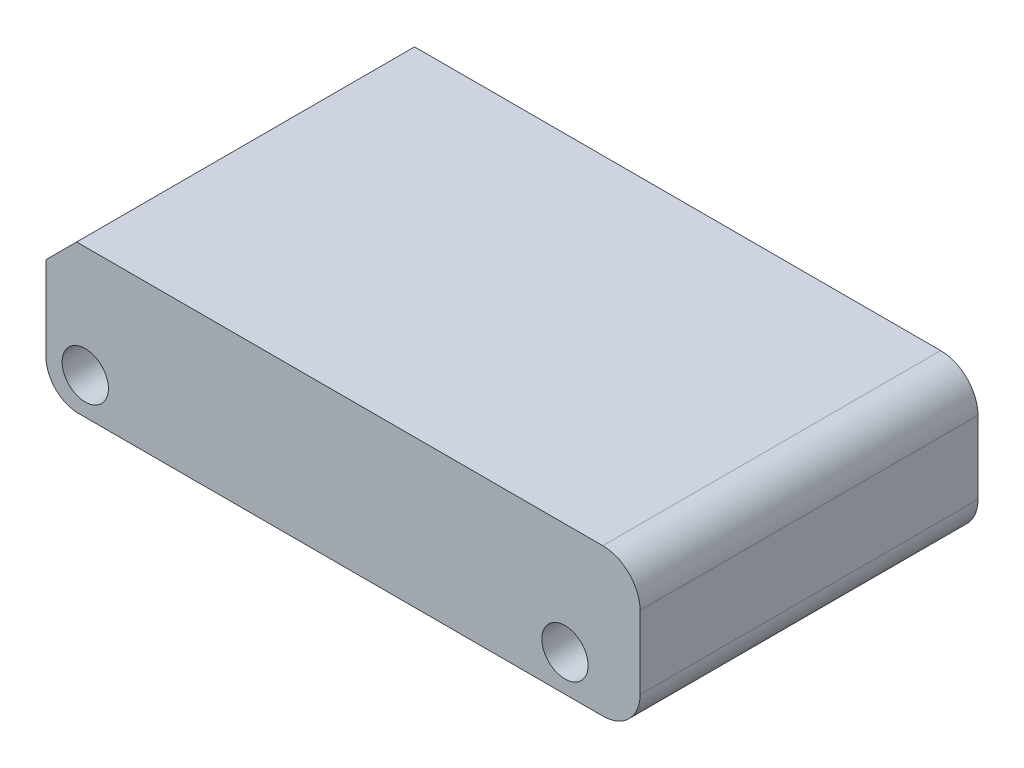
SolidWorks part; units mm, degrees
ref_plane "Front Plane" through (0, 0, 0) normal (0, 0, 1) x (1, 0, 0)
ref_plane "Top Plane" through (0, 0, 0) normal (0, 1, 0) x (1, 0, 0)
ref_plane "Right Plane" through (0, 0, 0) normal (1, 0, 0) x (0, 0, -1)
sketch "Sketch1" plane through (0, 0, 0) normal (0, 0, 1) x (1, 0, 0)
  line L0 (-88.8712, 30.9117) -> (57.4376, 30.9117)
  line L1 (-88.8712, 30.9117) -> (-97.3875, 22.3954)
  line L2 (-97.3875, 22.3954) -> (-97.3875, -1.0659)
  line L3 (-88.3272, -10.1263) -> (57.4376, -10.1263)
  line L4 (67.8192, 20.53) -> (67.8192, 0.2554)
  arc A0 (57.4376, -10.1263) -> (67.8192, 0.2554) centre (57.4376, 0.2554) ccw
  arc A1 (57.4376, 30.9117) -> (67.8192, 20.53) centre (57.4376, 20.53) cw
  circle A2 centre (-86.4729, 0) radius 6.4398
  arc A3 (-97.3875, -1.0659) -> (-88.3272, -10.1263) centre (-88.3272, -1.0659) ccw
  circle A5 centre (46.9391, 0) radius 6.4398
extrude "Boss-Extrude3" add sketch "Sketch1" against normal blind 93.98
